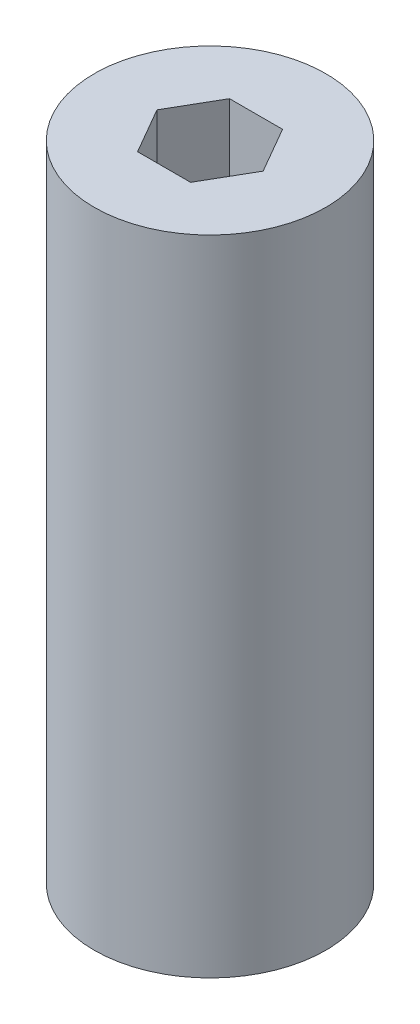
SolidWorks part; units mm, degrees
ref_plane "Front Plane" through (0, 0, 0) normal (0, 0, 1) x (1, 0, 0)
ref_plane "Top Plane" through (0, 0, 0) normal (0, 1, 0) x (1, 0, 0)
ref_plane "Right Plane" through (0, 0, 0) normal (1, 0, 0) x (0, 0, -1)
sketch "Sketch2" plane through (0, 0, 0) normal (0, 1, 0) x (1, 0, 0)
  circle A0 centre (0, 0) radius 16.002
  dimension "D1" = 32.004
extrude "Boss-Extrude1" add sketch "Sketch2" along normal blind 88.9 contours A0
sketch "Sketch3" plane through (0, 88.9, 0) normal (0, 1, 0) x (1, 0, 0)
  line L1 (7.3323, 0) -> (3.6662, 6.35)
  line L2 (3.6662, 6.35) -> (-3.6662, 6.35)
  line L3 (-3.6662, 6.35) -> (-7.3323, 0)
  line L4 (-7.3323, 0) -> (-3.6662, -6.35)
  line L5 (-3.6662, -6.35) -> (3.6662, -6.35)
  line L6 (3.6662, -6.35) -> (7.3323, 0)
  circle A0 centre (0, 0) radius 6.35 construction
extrude "Cut-Extrude1" cut sketch "Sketch3" against normal through all
